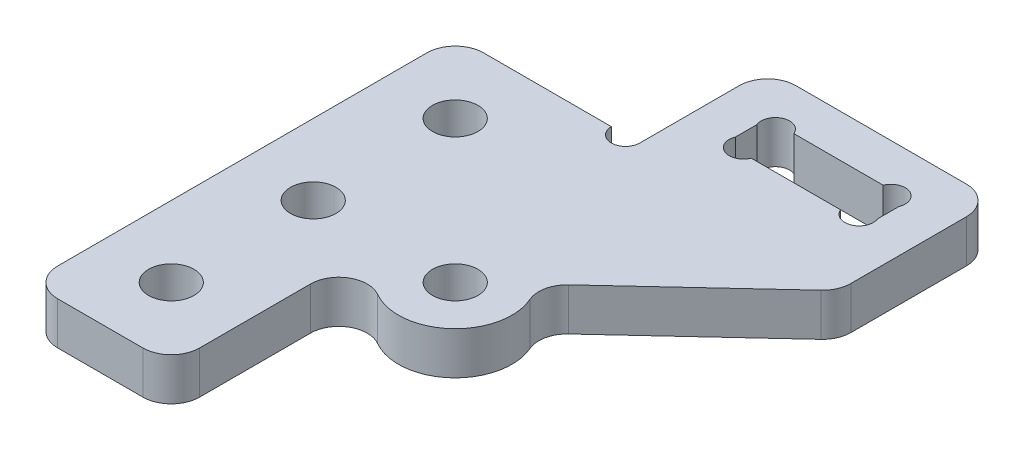
SolidWorks part; units mm, degrees
material "碳纤维"
ref_plane "前视基准面" through (0, 0, 0) normal (0, 0, 1) x (1, 0, 0)
ref_plane "上视基准面" through (0, 0, 0) normal (0, 1, 0) x (1, 0, 0)
ref_plane "右视基准面" through (0, 0, 0) normal (1, 0, 0) x (0, 0, -1)
sketch "草图1" plane through (0, 0, 0) normal (0, 1, 0) x (1, 0, 0)
  line L1 (-5, -15) -> (5, -15)
  line L2 (-5, -15) -> (-5, 15)
  line L3 (-5, 15) -> (5, 15)
  line L4 (5, -15) -> (5, 15)
  line L5 (0, 15) -> (0, -15) construction
  line L6 (-5, 0) -> (5, 0) construction
  circle A0 centre (0, 0) radius 1.6
  circle A1 centre (0, 10) radius 1.6
  circle A2 centre (0, -10) radius 1.6
  point P0 (0, 0)
  dimension "D1" = 10
  dimension "D2" = 3.2
  dimension "D3" = 30
  dimension "D4" = 10
extrude "凸台-拉伸1" add sketch "草图1" along normal blind 3
sketch "草图5" plane through (0, 0, 0) normal (0, -1, 0) x (1, 0, 0)
  line L1 (5, 15) -> (5, -15) construction
  line L2 (24, -13) -> (24, -24)
  line L5 (5, -15) -> (-5, -15) construction
  line L6 (11, -18) -> (21, -18)
  line L7 (11, -18) -> (11, -21)
  line L8 (11, -21) -> (21, -21)
  line L9 (21, -18) -> (21, -21)
  line L13 (24, -24) -> (8, -24)
  line L16 (5, -15) -> (8, -15)
  line L17 (8, -15) -> (8, -24)
  line L18 (5, -15) -> (5, 5.1962)
  line L19 (16, -21) -> (16, -24) construction
  line L20 (12.9312, -2.7218) -> (24, -13)
  circle A0 centre (10, 0) radius 1.6
  circle A1 centre (0, 0) radius 1.6 construction
  arc A2 (12.9312, -2.7218) -> (8, 3.4641) centre (10, 0) ccw
  arc A3 (5, 5.1962) -> (8, 3.4641) centre (7, 5.1962) ccw
  point P12 (11, -19.5)
  dimension "D9" = 10
  dimension "D10" = 8
  dimension "D11" = 2
  dimension "D1" = 10
  dimension "D2" = 3
  dimension "D3" = 3
  dimension "D4" = 19
  dimension "D5" = 9
  dimension "D6" = 2
  dimension "D7" = 3
  dimension "D8" = 3
extrude "凸台-拉伸4" add sketch "草图5" against normal up to surface (3 mm away) up to face at (0, 3, 0)
sketch "草图6" plane through (0, 0, 0) normal (0, -1, 0) x (1, 0, 0)
  line L0 (8, -15) -> (-5, -15) construction
  line L1 (11, -19.5) -> (16, -19.5) construction
  line L2 (11, -18) -> (11, -21) construction
  line L3 (16, -19.5) -> (16, -21) construction
  line L4 (11, -21) -> (21, -21) construction
  line L5 (21, -18.75) -> (21, -20.25) construction
  line L6 (21, -21) -> (21, -18) construction
  circle A0 centre (20.073, -18.375) radius 1
  circle A1 centre (11.927, -18.375) radius 1
  circle A2 centre (11.927, -20.625) radius 1
  circle A3 centre (20.073, -20.625) radius 1
  circle A4 centre (7, -15) radius 1
  dimension "D1" = 2
  dimension "D2" = 1.5
extrude "切除-拉伸1" cut sketch "草图6" against normal through all
fillet "圆角1" radius 2 7 edges at (8, 1.5, -24) (24, 1.5, -24) (24, 1.5, -13) (12.9312, 1.5, -2.7218) (5, 1.5, 15) (-5, 1.5, 15) (-5, 1.5, -15)
